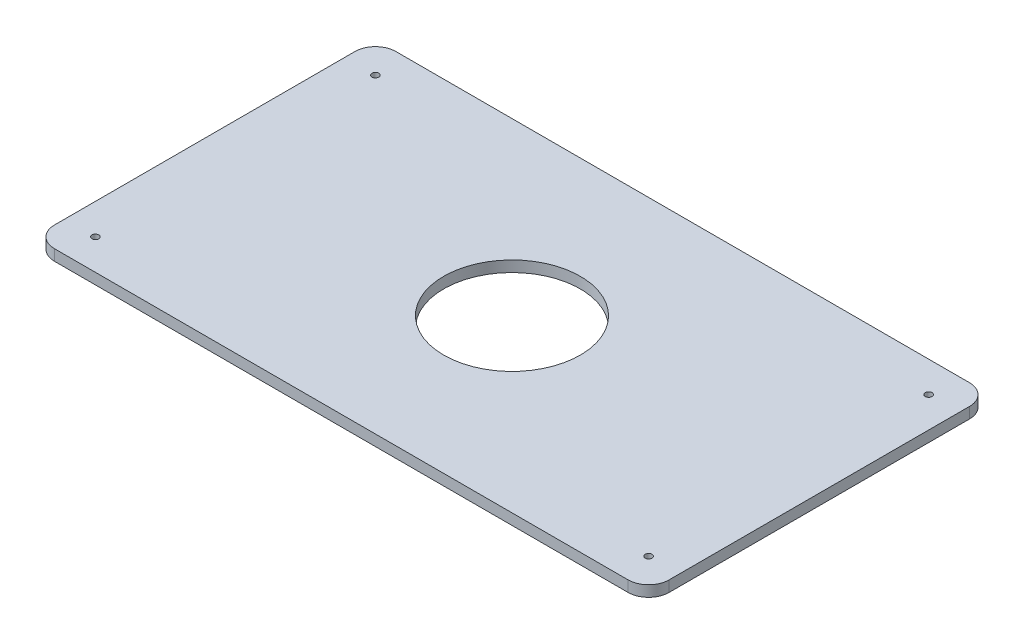
SolidWorks part; units mm, degrees
ref_plane "Alzado" through (0, 0, 0) normal (0, 0, 1) x (1, 0, 0)
ref_plane "Planta" through (0, 0, 0) normal (0, 1, 0) x (1, 0, 0)
ref_plane "Vista lateral" through (0, 0, 0) normal (1, 0, 0) x (0, 0, -1)
sketch "Croquis1" plane through (0, 0, 0) normal (0, 1, 0) x (1, 0, 0)
  line L0 (0, 125) -> (450, 125) construction
  line L1 (15, 0) -> (435, 0)
  line L2 (0, 15) -> (0, 235)
  line L3 (15, 250) -> (435, 250)
  line L4 (450, 15) -> (450, 235)
  line L5 (225, 125) -> (225, 227.5) construction
  line L6 (22.5, 227.5) -> (427.5, 227.5) construction
  line L7 (22.5, 227.5) -> (22.5, 22.5) construction
  line L8 (22.5, 22.5) -> (427.5, 22.5) construction
  line L9 (427.5, 227.5) -> (427.5, 22.5) construction
  circle A0 centre (225, 125) radius 50
  circle A1 centre (22.5, 227.5) radius 2.5
  circle A2 centre (427.5, 227.5) radius 2.5
  circle A3 centre (427.5, 22.5) radius 2.5
  circle A4 centre (22.5, 22.5) radius 2.5
  arc A5 (15, 0) -> (0, 15) centre (15, 15) cw
  arc A6 (435, 0) -> (450, 15) centre (435, 15) ccw
  arc A7 (435, 250) -> (450, 235) centre (435, 235) cw
  arc A8 (0, 235) -> (15, 250) centre (15, 235) cw
  point P17 (427.5, 125)
  point P18 (0, 0)
  point P19 (0, 0)
  point P21 (0, 0)
  point P24 (0, 0)
  point P29 (450, 250)
  point P32 (0, 250)
  dimension "D3" = 5
  dimension "D6" = 100
  dimension "D7" = 15
  dimension "D1" = 450
  dimension "D2" = 250
  dimension "D4" = 22.5
  dimension "D5" = 22.5
extrude "Saliente-Extruir1" add sketch "Croquis1" along normal blind 8
